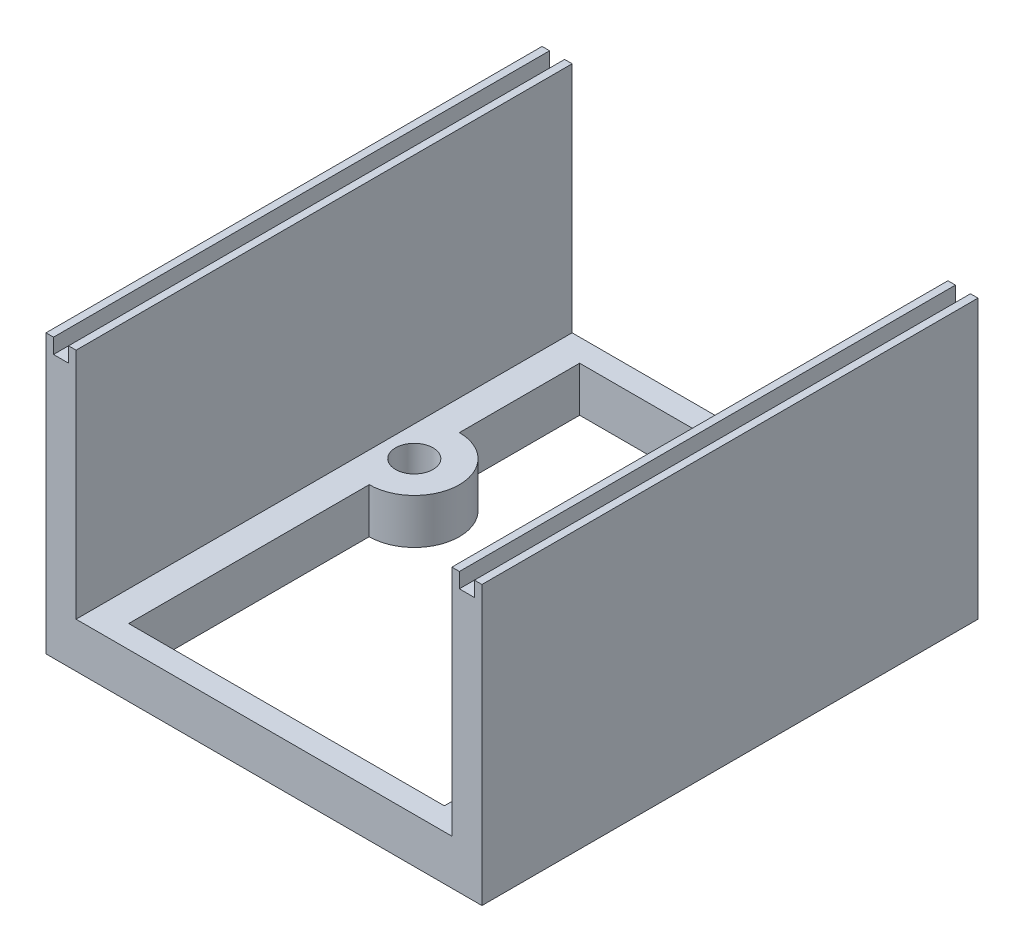
SolidWorks part; units mm, degrees
ref_plane "Front Plane" through (0, 0, 0) normal (0, 0, 1) x (1, 0, 0)
ref_plane "Top Plane" through (0, 0, 0) normal (0, 1, 0) x (1, 0, 0)
ref_plane "Right Plane" through (0, 0, 0) normal (1, 0, 0) x (0, 0, -1)
sketch "Sketch1" plane through (0, 0, 0) normal (0, 1, 0) x (1, 0, 0)
  line L0 (10.5, 7) -> (10.5, 15)
  line L1 (-12, -16.5) -> (12, -16.5)
  line L2 (-12, -16.5) -> (-12, 16.5)
  line L3 (-12, 16.5) -> (12, 16.5)
  line L4 (12, -16.5) -> (12, 16.5)
  line L5 (0, 16.5) -> (0, -16.5) construction
  line L6 (-12, 0) -> (12, 0) construction
  line L7 (-10.5, -15) -> (10.5, -15)
  line L8 (-10.5, -15) -> (-10.5, 1)
  line L9 (-10.5, 15) -> (10.5, 15)
  line L10 (10.5, -15) -> (10.5, 1)
  line L11 (0, 15) -> (0, -15) construction
  line L12 (-10.5, 0) -> (10.5, 0) construction
  line L13 (-10.5, 7) -> (-10.5, 15)
  arc A3 (10.5, 7) -> (10.5, 1) centre (10.5, 4) ccw
  arc A4 (-10.5, 1) -> (-10.5, 7) centre (-10.5, 4) ccw
  point P0 (0, 0)
  point P4 (0, 0)
  dimension "D5" = 12.5
  dimension "D1" = 33
  dimension "D2" = 24
  dimension "D3" = 21
  dimension "D4" = 30
  dimension "D6" = 1.5
extrude "Boss-Extrude2" add sketch "Sketch1" along normal blind 3
sketch "Sketch2" plane through (0, 3, 0) normal (0, 1, 0) x (1, 0, 0)
  circle A0 centre (-10.5, 4) radius 1.25
  circle A1 centre (10.5, 4) radius 1.25
  dimension "D1" = 2.5
extrude "Cut-Extrude2" cut sketch "Sketch2" against normal blind 3
sketch "Sketch4" plane through (0, 3, 0) normal (0, 1, 0) x (1, 0, 0)
  line L1 (-12, -16.5) -> (-14.5, -16.5)
  line L2 (-12, -16.5) -> (-12, 16.5)
  line L3 (-12, 16.5) -> (-14.5, 16.5)
  line L4 (-14.5, -16.5) -> (-14.5, 16.5)
  line L5 (12, 16.5) -> (14.5, 16.5)
  line L6 (12, 16.5) -> (12, -16.5)
  line L7 (12, -16.5) -> (14.5, -16.5)
  line L8 (14.5, 16.5) -> (14.5, -16.5)
  dimension "D1" = 2.5
extrude "Boss-Extrude3" add sketch "Sketch4" against normal blind 3
sketch "Sketch5" plane through (0, 3, 0) normal (0, 1, 0) x (1, 0, 0)
  line L0 (-14.5, -16.5) -> (14.5, -16.5) construction
  line L1 (-14.5, 16.5) -> (-12.5, 16.5)
  line L2 (-14.5, 16.5) -> (-14.5, -16.5)
  line L3 (-14.5, -16.5) -> (-12.5, -16.5)
  line L4 (-12.5, 16.5) -> (-12.5, -16.5)
  line L5 (14.5, 16.5) -> (-14.5, 16.5) construction
  line L6 (14.5, -16.5) -> (12.5, -16.5)
  line L7 (14.5, -16.5) -> (14.5, 16.5)
  line L8 (14.5, 16.5) -> (12.5, 16.5)
  line L9 (12.5, -16.5) -> (12.5, 16.5)
  dimension "D1" = 2
extrude "Boss-Extrude4" add sketch "Sketch5" along normal blind 15.5
sketch "Sketch6" plane through (0, 18.5, 0) normal (0, 1, 0) x (1, 0, 0)
  line L0 (14.5, 16.5) -> (12.5, 16.5) construction
  line L1 (13, 16.5) -> (14, 16.5)
  line L2 (13, 16.5) -> (13, -16.5)
  line L3 (13, -16.5) -> (14, -16.5)
  line L4 (14, 16.5) -> (14, -16.5)
  line L5 (12.5, -16.5) -> (14.5, -16.5) construction
  line L6 (-12.5, 16.5) -> (-14.5, 16.5) construction
  line L7 (-14, 16.5) -> (-13, 16.5)
  line L8 (-14, 16.5) -> (-14, -16.5)
  line L9 (-14, -16.5) -> (-13, -16.5)
  line L10 (-13, 16.5) -> (-13, -16.5)
  line L11 (-14.5, -16.5) -> (-12.5, -16.5) construction
  line L12 (-14.5, 16.5) -> (-14, 16.5) construction
  line L13 (-13, 16.5) -> (-12.5, 16.5) construction
  line L14 (12.5, 16.5) -> (13, 16.5) construction
  line L15 (14, 16.5) -> (14.5, 16.5) construction
  dimension "D1" = 1
extrude "Cut-Extrude3" cut sketch "Sketch6" against normal blind 1
